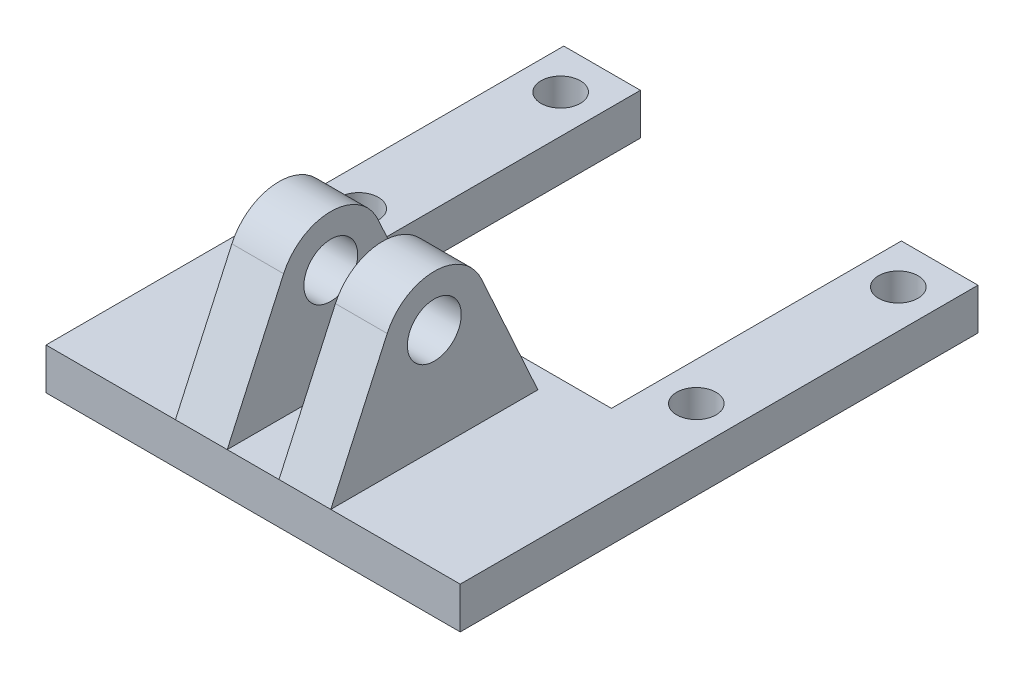
SolidWorks part; units mm, degrees
ref_plane "Front Plane" through (0, 0, 0) normal (0, 0, 1) x (1, 0, 0)
ref_plane "Top Plane" through (0, 0, 0) normal (0, 1, 0) x (1, 0, 0)
ref_plane "Right Plane" through (0, 0, 0) normal (1, 0, 0) x (0, 0, -1)
sketch "Sketch1" plane through (0, 0, 0) normal (0, 1, 0) x (1, 0, 0)
  line L0 (-12.7, 0) -> (-12.7, 31.75)
  line L1 (-12.7, 31.75) -> (-8.001, 31.75)
  line L2 (-8.001, 31.75) -> (-8.001, 13.97)
  line L3 (-8.001, 13.97) -> (8.001, 13.97)
  line L4 (8.001, 13.97) -> (8.001, 31.75)
  line L5 (8.001, 31.75) -> (12.7, 31.75)
  line L6 (12.7, 31.75) -> (12.7, 0)
  line L7 (12.7, 0) -> (-12.7, 0)
  line L8 (-10.3505, 31.75) -> (-10.3505, 0) construction
  line L9 (10.3505, 31.75) -> (10.3505, 0) construction
  circle A0 centre (-10.3505, 29.21) radius 1.2065
  circle A1 centre (-10.3505, 16.8275) radius 1.2065
  circle A2 centre (10.3505, 29.21) radius 1.2065
  circle A3 centre (10.3505, 16.8275) radius 1.2065
  dimension "D2" = 2.413
  dimension "D1" = 25.4
  dimension "D3" = 31.75
  dimension "D4" = 12.3825
  dimension "D5" = 20.701
  dimension "D6" = 17.78
  dimension "D7" = 2.54
extrude "Boss-Extrude1" add sketch "Sketch1" along normal blind 2.54
sketch "Sketch2" plane through (0, 0, 0) normal (1, 0, 0) x (0, 0, -1)
  line L0 (12.7, 2.54) -> (6.35, 16.51)
  line L1 (0, 2.54) -> (31.75, 2.54) construction
  line L2 (6.35, 16.51) -> (0, 2.54)
  line L3 (12.7, 2.54) -> (0, 2.54)
  line L4 (0, 2.54) -> (-0.0326, 2.6981)
  circle A0 centre (6.35, 8.89) radius 1.651
  dimension "D1" = 3.302
  dimension "D2" = 12.7
  dimension "D3" = 13.97
  dimension "D4" = 6.35
extrude "Boss-Extrude2" add sketch "Sketch2" along normal mid plane 9.525 contours L3 L0 L2 | A0
sketch "Sketch3" plane through (0, 2.54, 0) normal (0, 1, 0) x (1, 0, 0)
  line L0 (4.7625, 0) -> (-4.7625, 0) construction
  line L1 (-1.5875, 0) -> (1.5875, 0)
  line L2 (-1.5875, 0) -> (-1.5875, 12.7)
  line L3 (-1.5875, 12.7) -> (1.5875, 12.7)
  line L4 (1.5875, 0) -> (1.5875, 12.7)
  line L5 (4.7625, 12.7) -> (-4.7625, 12.7) construction
  dimension "D1" = 3.175
extrude "Cut-Extrude1" cut sketch "Sketch3" along normal up to vertex
fillet "Fillet1" radius 3.175 2 edges at (3.175, 16.51, -6.35) (-3.175, 16.51, -6.35)
